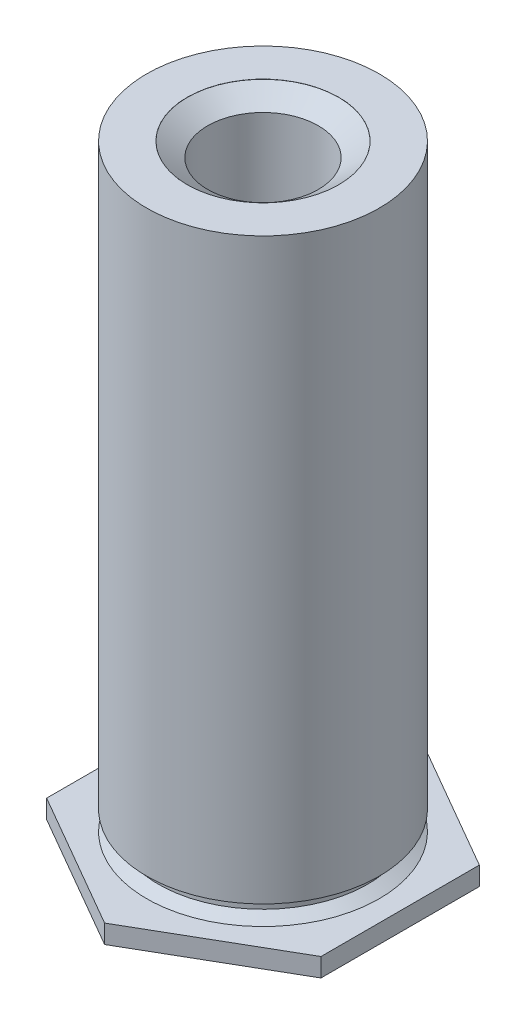
SolidWorks part; units mm, degrees
revolve "Body" add sketch "BodySke"
sketch "BodySke" plane through (0, 0, 0) normal (0, 0, 1) x (1, 0, 0)
  line L0 (2.6924, 0) -> (3.683, 0)
  line L1 (3.683, 0) -> (3.683, 0.4308)
  line L2 (3.683, 0.4308) -> (2.6924, 0.4308)
  line L3 (1.2802, 14.2748) -> (1.2802, 7.4168)
  line L4 (2.6924, 0.8831) -> (2.4232, 0.8831)
  line L5 (2.4232, 0.8831) -> (2.4232, 0.5862)
  line L6 (2.6924, 0.0025) -> (2.6924, 0)
  line L7 (1.016, 13.4823) -> (3.6522, 13.4823) construction
  line L8 (2.6924, 14.2748) -> (1.2802, 14.2748)
  line L9 (0, 0) -> (0, 15.24) construction
  line L10 (2.6924, 0.0025) -> (0, 0.0025)
  line L11 (2.6924, 14.2748) -> (2.6924, 0.8831)
  line L12 (0, 7.4168) -> (1.2802, 7.4168)
  line L13 (0, 7.4168) -> (0, 0.0025)
  line L14 (1.016, 7.4168) -> (3.6522, 7.4168) construction
  line L15 (1.016, 14.2723) -> (3.6522, 14.2723) construction
  line L16 (2.6924, 0.4308) -> (2.4232, 0.5862)
  dimension "D1" = 0.0025
  dimension "E_dia" = 7.366
  dimension "D2" = 30
  dimension "C_dia" = 5.3848
  dimension "Thread_min" = 2.5603
  dimension "Clinching_ht" = 0.4308
  dimension "Advance" = 0.7925
  dimension "Length" = 14.2748
  dimension "Thread_limit" = 6.858
  dimension "Thread_depth" = 6.858
  dimension "Drill_depth" = 0.0025
  dimension "Groove_wid" = 0.4523
  dimension "Groove_dia" = 4.8463
cosmetic thread "ThreadCosmetic" [suppressed]
revolve "EndChamfer" cut sketch "EndChamferSke" angle 360 about L0
sketch "EndChamferSke" plane through (0, 0, 0) normal (0, 0, 1) x (1, 0, 0)
  line L0 (0, -2.54) -> (0, 7.62) construction
  line L1 (0, 0) -> (0, 15.24) construction
  line L2 (1.7551, 14.2723) -> (1.7551, 14.5288)
  line L4 (1.7551, 14.2723) -> (1.7526, 14.2723)
  line L6 (1.7526, 14.2723) -> (1.2802, 13.9416)
  line L8 (1.2802, 13.9416) -> (1.2802, 14.5288)
  line L9 (1.7551, 14.5288) -> (1.2802, 14.5288)
  line L10 (2.6924, 14.2748) -> (-2.6924, 14.2748) construction
  dimension "Inset" = 0.0025
  dimension "D1" = 0.254
  dimension "D2" = 34.99
  dimension "Thread_nominal" = 3.5052
  dimension "Thread_min" = 2.5603
revolve "TapDrill" cut sketch "TapDriSke" angle 360 about L0
sketch "TapDriSke" plane through (0, 0, 0) normal (0, 0, 1) x (1, 0, 0)
  line L0 (0, 0) -> (0, 15.24) construction
  line L1 (0, 0) -> (0, 15.24) construction
  line L2 (1.2802, 3.4544) -> (1.2802, 14.2748)
  line L3 (2.6924, 14.2748) -> (-2.6924, 14.2748) construction
  line L4 (1.2802, 3.4544) -> (0, 2.9241)
  line L5 (0, 2.9241) -> (0, 14.2748)
  line L6 (0, 14.2748) -> (1.2802, 14.2748)
  line L7 (1.2802, 7.4168) -> (1.2802, 14.2748) construction
  line L8 (0, 2.9241) -> (-1.2802, 3.4544) construction
  line L9 (-1.2802, 14.2748) -> (-1.2802, 7.4168) construction
  dimension "D1" = 135
  dimension "Depth" = 10.8204
ref_plane "Plane1" through (0, 0, 0) normal (0, 0, 1) x (1, 0, 0)
ref_plane "Plane2" through (0, 0, 0) normal (0, 1, 0) x (1, 0, 0)
ref_plane "Plane3" through (0, 0, 0) normal (1, 0, 0) x (0, 0, -1)
ref_plane "Plane4" through (0, -0.5486, 0) normal (0, 1, 0) x (-1, 0, 0)
sketch "ThdSchSke" plane through (0, 0, 0) normal (0, 0, 1) x (1, 0, 0)
  line L0 (0, -5.08) -> (0, 7.62) construction
  line L1 (0, 0) -> (0, 15.24) construction
  line L2 (0, 14.2723) -> (1.7526, 14.2723) construction
  line L4 (1.7526, 14.2723) -> (1.2802, 14.6031)
  line L5 (1.7551, 14.2723) -> (-1.7551, 14.2723) construction
  line L6 (1.7526, 14.2723) -> (1.2802, 13.9415)
  line L7 (1.2802, 14.6031) -> (1.2802, 13.9415)
  dimension "Thread_nominal" = 3.5052
  dimension "Thread_min" = 2.5603
revolve "ThreadSchematic" [suppressed] cut sketch "ThdSchSke" angle 360 about L0
pattern_linear "ThdSchPat" [suppressed]
sketch "HexDieSke" plane through (0, 0.4308, 0) normal (0, 1, 0) x (-1, 0, 0)
  line L0 (0, 3.6662) -> (3.175, 1.8331)
  line L1 (3.175, 1.8331) -> (3.175, -1.8331)
  line L2 (3.175, -1.8331) -> (0, -3.6662)
  line L3 (0, -3.6662) -> (-3.175, -1.8331)
  line L4 (-3.175, -1.8331) -> (-3.175, 1.8331)
  line L5 (-3.175, 1.8331) -> (0, 3.6662)
  circle A1 centre (0, 0) radius 3.175 construction
  circle A2 centre (0, 0) radius 3.6662 construction
  circle A3 centre (0, 0) radius 3.6957
extrude "HexDie" cut sketch "HexDieSke" against normal blind 0.4308
equation "' \"Length@BodySke\" = 0.562"
equation "' \"C_dia@BodySke\" = 0.212"
equation "' \"Thread_depth@BodySke\" = 0.27 'always explicit"
equation "' \"Drill_depth@BodySke\" = 0.0001 'implicit, or explicit"
equation "' \"Width_across_flats@HexDieSke\" = 0.25"
equation "' \"Advance@BodySke\" = 0.0312"
equation "' \"Thread_min@BodySke\" = 0.1008"
equation "' \"Thread_nominal@ThreadCosmetic\" = 0.138"
equation "\"B_dia@EndChamferSke\" = \"Thread_nominal@ThreadCosmetic\" + 0.0002"
equation "\"E_dia@BodySke\" = \"Width_across_flats@HexDieSke\" * 1.16"
equation "\"Clinching_ht@BodySke\" = \"C_dia@BodySke\" * 0.08"
equation "\"Groove_dia@BodySke\" = \"C_dia@BodySke\" * 0.9"
equation "\"Groove_wid@BodySke\" = \"Clinching_ht@BodySke\" * 1.05"
equation "\"Thread_limit@BodySke\" = ((sgn( \"Length@BodySke\" - 0.0002 - \"Thread_depth@BodySke\" )-1)*( \"Length@BodySke\" - 0.0002 - \"Thread_depth@BodySke\" ))/-2+ \"Thread_depth@BodySke\""
equation "\"Depth@TapDriSke\" = \"Thread_limit@BodySke\" + \"Advance@BodySke\" * 5"
equation "\"Depth@TapDriSke\" = ((sgn( \"Depth@TapDriSke\" - \"Drill_depth@BodySke\" )+1)*( \"Depth@TapDriSke\" - \"Drill_depth@BodySke\" ))/2 +\"Drill_depth@BodySke\""
equation "\"Depth@HexDie\" = \"Clinching_ht@BodySke\""
equation "\"OD@HexDieSke\" =  \"Width_across_flats@HexDieSke\" * 1.16 + 0.001"
equation "\"Thread_nominal@EndChamferSke\" = \"Thread_nominal@ThreadCosmetic\""
equation "\"Thread_min@EndChamferSke\" = \"Thread_min@BodySke\""
equation "\"D2@EndChamferSke\" = \"Vee_angle@ThdSchSke\" / 2 - 0.01"
equation "\"Thread_nominal@ThdSchSke\" = \"Thread_nominal@ThreadCosmetic\""
equation "\"Thread_min@ThdSchSke\" = \"Thread_min@BodySke\""
equation "\"Num_threads@ThdSchPat\" = int(  ( \"Thread_limit@BodySke\" - \"Inset@EndChamferSke\" ) / \"Advance@BodySke\" + 0.999 )  + 1"
equation "\"Advance@ThdSchPat\" = (  \"Thread_limit@BodySke\" - \"Inset@EndChamferSke\" ) /  (\"Num_threads@ThdSchPat\" - 1) 'relax it"
